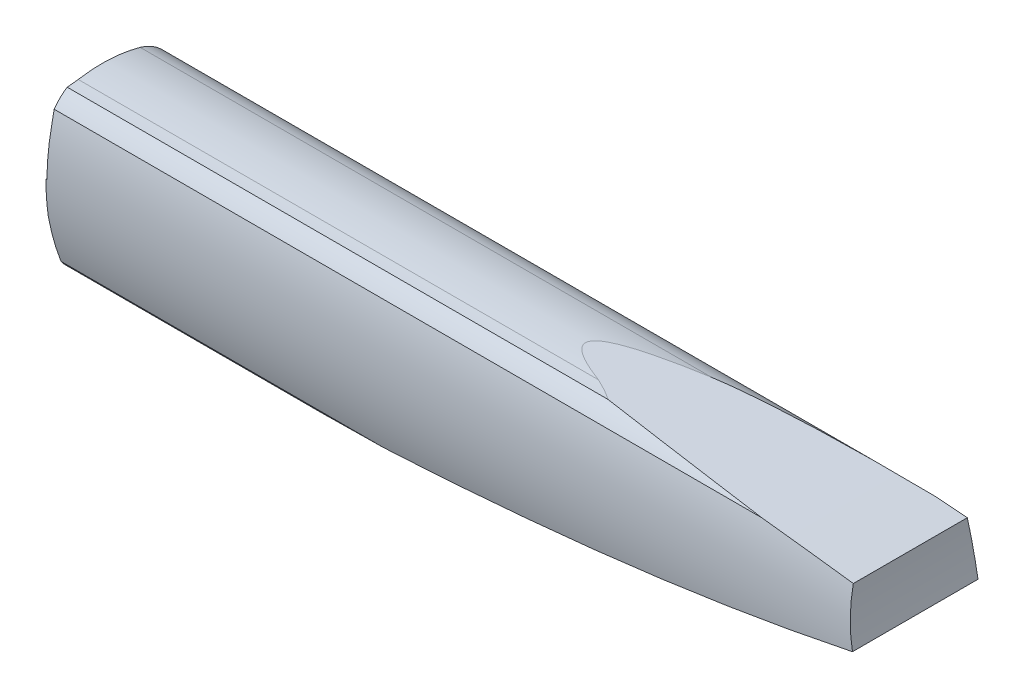
SolidWorks part; units mm, degrees
ref_plane "Front Plane" through (0, 0, 0) normal (0, 0, 1) x (1, 0, 0)
ref_plane "Top Plane" through (0, 0, 0) normal (0, 1, 0) x (1, 0, 0)
ref_plane "Right Plane" through (0, 0, 0) normal (1, 0, 0) x (0, 0, -1)
sketch "Sketch1" plane through (0, 0, 0) normal (0, 0, 1) x (1, 0, 0)
  arc A0 (-192.6294, 0) -> (-73.9915, 55.3217) centre (0.6853, -259.6942) cw
  arc A1 (-73.9915, 55.3217) -> (535.7856, 33.7196) centre (72.3044, -4432.1785) cw
  arc A2 (535.7856, 33.7196) -> (539.3178, -7.795) centre (823.0927, 37.2576) ccw
  arc A3 (539.3178, -7.795) -> (-66.5683, -71.6141) centre (-68.1444, 2851.3439) cw
  arc A4 (-192.6294, 0) -> (-66.5683, -71.6141) centre (-55.5394, 94.5588) ccw
extrude "Boss-Extrude1" add sketch "Sketch1" along normal blind 100
sketch "Sketch2" plane through (0, 0, 0) normal (1, 0, 0) x (0, 0, -1)
  arc A0 (-65.4472, 54.8304) -> (-92.9565, 40.6004) centre (-65.0756, 20.4068) ccw
  arc A1 (-92.9565, 40.6004) -> (-88.9673, -61.9502) centre (74.239, -4.2486) ccw
  arc A2 (-88.9673, -61.9502) -> (-75.5891, -72.2161) centre (-66.8398, -46.9643) ccw
  arc A3 (-75.5891, -72.2161) -> (-173.3785, -75.4078) centre (-126.0797, -24.9172) cw
  arc A4 (-173.3785, -75.4078) -> (-135.2629, 60.9401) centre (86.0317, -74.4236) cw
  arc A5 (-135.2629, 60.9401) -> (-61.3269, 89.0039) centre (-51.8166, -47.4784) cw
  arc A6 (-61.3269, 89.0039) -> (-65.4472, 54.8304) centre (778.5841, -29.5983) ccw
extrude "Cut-Extrude3" cut sketch "Sketch2" against normal through all both and the other way through all
sketch "Sketch3" plane through (0, 0, 0) normal (1, 0, 0) x (0, 0, -1)
  arc A0 (-74.2083, 50.8866) -> (-26.7131, 48.511) centre (-56.0106, -61.2597) cw
  arc A1 (-26.7131, 48.511) -> (-7.715, 36.1895) centre (-36.3575, 12.8336) cw
  arc A2 (-8.6781, -61.6499) -> (-29.5113, -74.3603) centre (-30.579, -49.1815) cw
  arc A3 (-74.2083, 50.8866) -> (12.3195, 83.1167) centre (-99.8212, 251.9147) cw
  arc A4 (12.3195, 83.1167) -> (85.2864, -42.1041) centre (302.1155, 168.113) ccw
  arc A5 (85.2864, -42.1041) -> (-29.5113, -74.3603) centre (9.4865, 7.2561) cw
  arc A6 (-7.715, 36.1895) -> (-8.6781, -61.6499) centre (-213.3664, -10.7106) cw
extrude "Cut-Extrude5" cut sketch "Sketch3" against normal through all both and the other way through all
sketch "Sketch4" plane through (0, 0, 0) normal (0, 0, 1) x (1, 0, 0)
  line L0 (-79.2014, 32.882) -> (-79.2014, -3.1227)
  line L1 (-79.2014, -3.1227) -> (-222.7681, 1.8142)
  line L2 (-222.7681, 1.8142) -> (-233.2223, 17.1102)
  line L3 (-233.2223, 17.1102) -> (-80.5294, 72.4569)
  line L4 (-80.5294, 72.4569) -> (-79.2014, 32.882)
extrude "Cut-Extrude7" cut sketch "Sketch4" against normal through all both and the other way through all
sketch "Sketch7" plane through (0, 0, 0) normal (0, 0, 1) x (1, 0, 0)
  line L0 (-79.8805, -28.1003) -> (-77.6227, -75.1317)
  line L1 (-77.6227, -75.1317) -> (-149.5911, -109.1597)
  line L2 (-149.5911, -109.1597) -> (-180.7326, -79.4686)
  line L3 (-249.8177, 15.8164) -> (-180.7326, -79.4686)
  line L4 (-244.4522, 8.416) -> (-79.8805, 8.416)
  line L5 (-79.8805, 8.416) -> (-79.8805, -28.1003)
extrude "Cut-Extrude9" cut sketch "Sketch7" against normal through all both and the other way through all contours L5 L4 L3 L2 L1 L0
